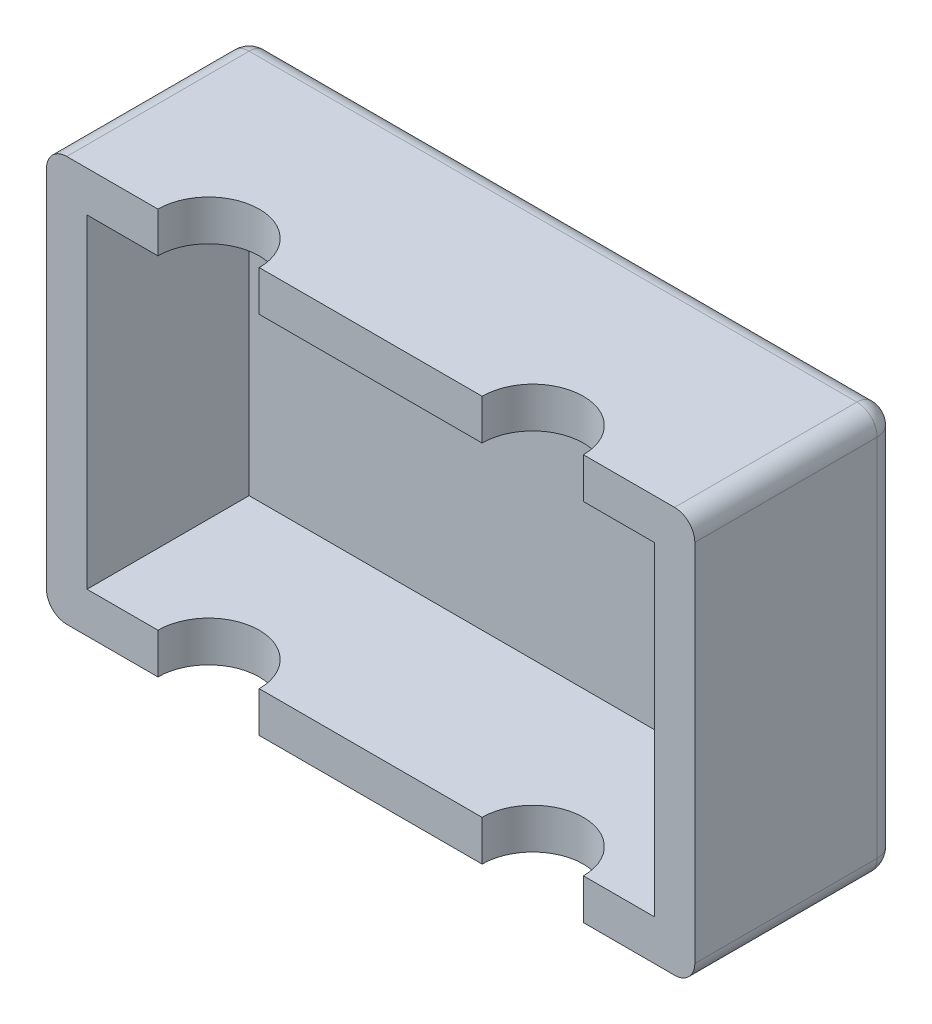
SolidWorks part; units mm, degrees
ref_plane "Front Plane" through (0, 0, 0) normal (0, 0, 1) x (1, 0, 0)
ref_plane "Top Plane" through (0, 0, 0) normal (0, 1, 0) x (1, 0, 0)
ref_plane "Right Plane" through (0, 0, 0) normal (1, 0, 0) x (0, 0, -1)
sketch "Sketch1" plane through (0, 0, 0) normal (0, 0, 1) x (1, 0, 0)
  line L1 (-30, 20) -> (30, 20)
  line L2 (-32, 18) -> (-32, -18)
  line L3 (-30, -20) -> (30, -20)
  line L4 (32, 18) -> (32, -18)
  line L5 (-32, 20) -> (32, -20) construction
  line L6 (-32, -20) -> (32, 20) construction
  arc A0 (-32, -18) -> (-30, -20) centre (-30, -18) ccw
  arc A1 (30, -20) -> (32, -18) centre (30, -18) ccw
  arc A2 (30, 20) -> (32, 18) centre (30, 18) cw
  arc A3 (-30, 20) -> (-32, 18) centre (-30, 18) ccw
  point P0 (0, 0)
  dimension "D3" = 2
  dimension "D1" = 40
  dimension "D2" = 64
extrude "Boss-Extrude1" add sketch "Sketch1" along normal blind 20
fillet "Fillet1" radius 2 8 edges at (31.4142, 19.4142, 0) (32, 0, 0) (31.4142, -19.4142, 0) (0, -20, 0) (-31.4142, -19.4142, 0) (-32, 0, 0) (-31.4142, 19.4142, 0) (0, 20, 0)
shell "Shell1" thickness 4
sketch "Sketch2" plane through (0, 0, 0) normal (0, 1, 0) x (1, 0, 0)
  line L0 (28, -20) -> (-28, -20) construction
  line L1 (-16, -20) -> (16, -20) construction
  circle A0 centre (-16, -20) radius 5
  circle A1 centre (16, -20) radius 5
  point P4 (0, -20)
  dimension "D1" = 10
  dimension "D2" = 32
extrude "Cut-Extrude1" cut sketch "Sketch2" against normal through all both and the other way through all
equation "\"HoleSize\"= 10"
equation "\"D1@Sketch2\"=\"HoleSize\""
